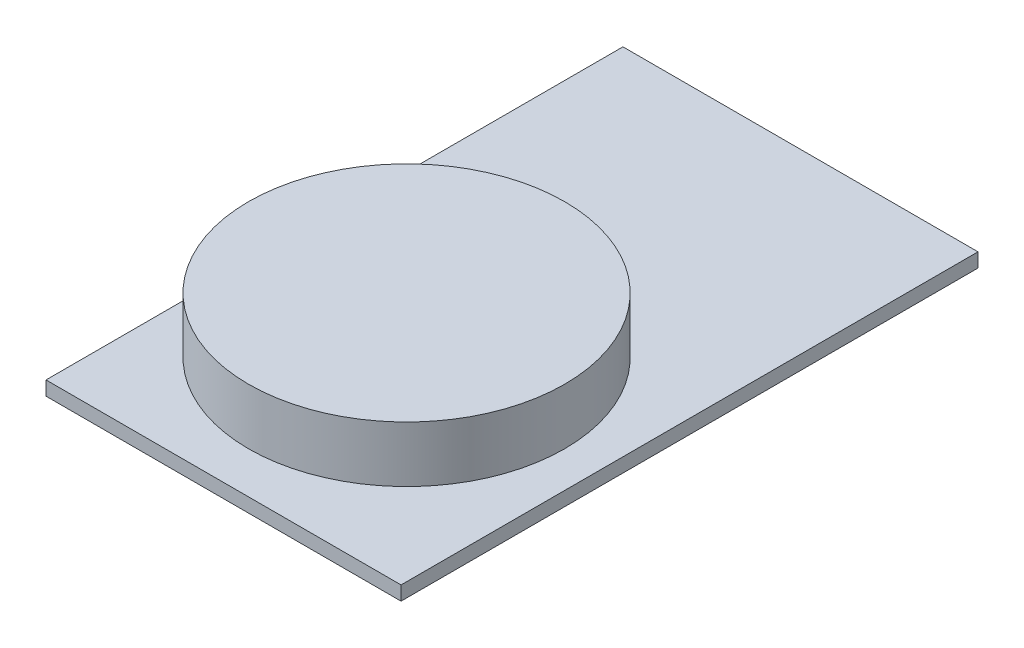
SolidWorks part; units mm, degrees
ref_plane "Front Plane" through (0, 0, 0) normal (0, 0, 1) x (1, 0, 0)
ref_plane "Top Plane" through (0, 0, 0) normal (0, 1, 0) x (1, 0, 0)
ref_plane "Right Plane" through (0, 0, 0) normal (1, 0, 0) x (0, 0, -1)
sketch "Sketch1" plane through (0, 0, 0) normal (0, 1, 0) x (1, 0, 0)
  circle A0 centre (0, 0) radius 71.25
  dimension "D1" = 142.5
extrude "Boss-Extrude1" add sketch "Sketch1" along normal mid plane 25.2
sketch "Sketch2" plane through (0, -12.6, 0) normal (0, -1, 0) x (1, 0, 0)
  line L1 (-72.5, 90) -> (87.5, 90)
  line L2 (-72.5, 90) -> (-72.5, -170)
  line L3 (-72.5, -170) -> (87.5, -170)
  line L4 (87.5, 90) -> (87.5, -170)
  circle A0 centre (0, 0) radius 71.25 construction
  circle A1 centre (0, 0) radius 71.25 construction
  dimension "D1" = 90
  dimension "D2" = 72.5
  dimension "D3" = 87.5
  dimension "D4" = 170
extrude "Boss-Extrude2" add sketch "Sketch2" along normal blind 6.35
